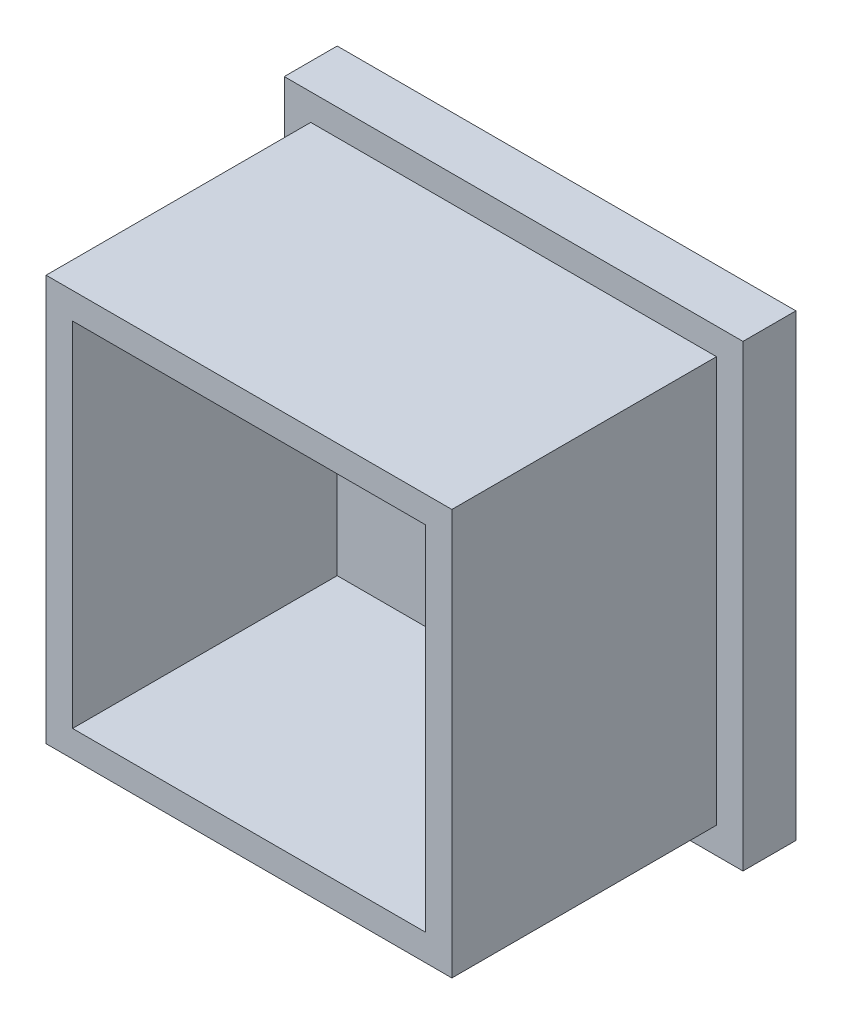
SolidWorks part; units mm, degrees
ref_plane "Alzado" through (0, 0, 0) normal (0, 0, 1) x (1, 0, 0)
ref_plane "Planta" through (0, 0, 0) normal (0, 1, 0) x (1, 0, 0)
ref_plane "Vista lateral" through (0, 0, 0) normal (1, 0, 0) x (0, 0, -1)
sketch "Croquis1" plane through (0, 0, 0) normal (0, 0, 1) x (1, 0, 0)
  line L1 (0, 0) -> (26, 0)
  line L2 (0, 0) -> (0, -26)
  line L3 (0, -26) -> (26, -26)
  line L4 (26, 0) -> (26, -26)
  dimension "D1" = 26
  dimension "D2" = 26
extrude "Saliente-Extruir1" add sketch "Croquis1" along normal blind 3
sketch "Croquis2" plane through (0, 0, 3) normal (0, 0, 1) x (1, 0, 0)
  line L1 (26, -26) -> (26, 0) construction
  line L3 (0, 0) -> (0, -26) construction
  line L4 (1.5, -1.5) -> (24.5, -1.5)
  line L5 (1.5, -1.5) -> (1.5, -24.5)
  line L6 (1.5, -24.5) -> (24.5, -24.5)
  line L7 (24.5, -1.5) -> (24.5, -24.5)
  line L8 (3, -3) -> (3, -23)
  line L9 (3, -23) -> (23, -23)
  line L10 (23, -3) -> (23, -23)
  line L11 (3, -3) -> (23, -3)
  dimension "D1" = 23
  dimension "D2" = 1.5
  dimension "D3" = 1.5
extrude "Saliente-Extruir2" add sketch "Croquis2" along normal blind 15
